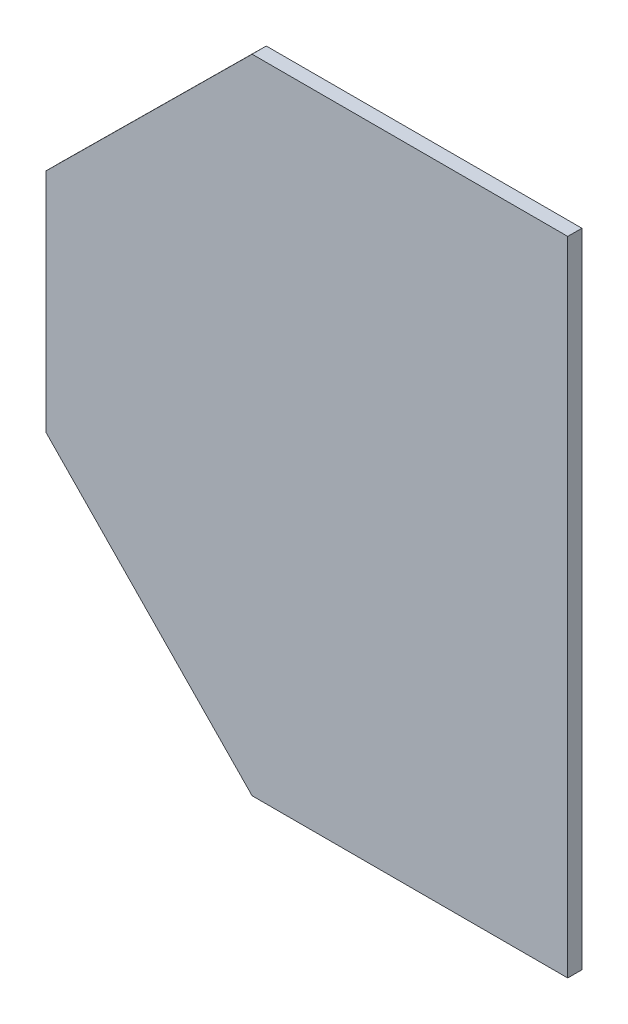
SolidWorks part; units mm, degrees
material "ASTM A500 Grade B"
ref_plane "Front Plane" through (0, 0, 0) normal (0, 0, 1) x (1, 0, 0)
ref_plane "Top Plane" through (0, 0, 0) normal (0, 1, 0) x (1, 0, 0)
ref_plane "Right Plane" through (0, 0, 0) normal (1, 0, 0) x (0, 0, -1)
sketch "Sketch1" plane through (0, 0, 0) normal (0, 0, 1) x (1, 0, 0)
  line L0 (-4.281, -146.7903) -> (-216.4881, -146.7903)
  line L1 (-4.281, -2487.2903) -> (-4.281, 2625.5097) construction
  line L2 (-216.4881, 285.0097) -> (-354.9957, 147.8379)
  line L4 (-354.9957, 147.8379) -> (-354.9957, -4.5621)
  line L6 (-354.9957, -4.5621) -> (-216.4881, -146.7903)
  line L7 (-216.4881, 285.0097) -> (-4.281, 285.0097)
  line L8 (-4.281, 285.0097) -> (-4.281, -146.7903)
  line L9 (-60.0478, 69.1097) -> (35.4026, 69.1097) construction
  line L10 (-60.0478, 119.9097) -> (-60.0478, 18.3097) construction
  dimension "D1" = 215.9
  dimension "D2" = 215.9
  dimension "D3" = 152.4
extrude "Boss-Extrude1" add sketch "Sketch1" along normal blind 9.525
